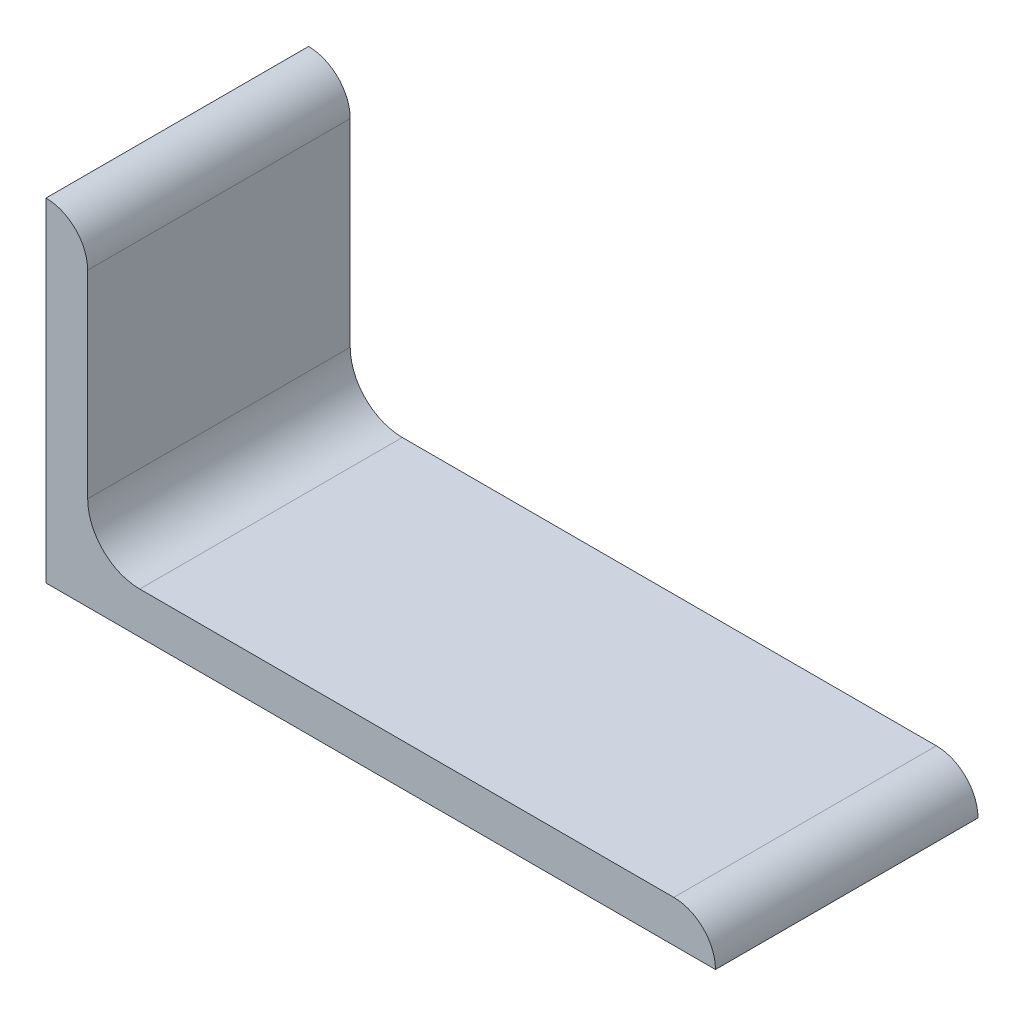
SolidWorks part; units mm, degrees
ref_plane "Alzado" through (0, 0, 0) normal (0, 0, 1) x (1, 0, 0)
ref_plane "Planta" through (0, 0, 0) normal (0, 1, 0) x (1, 0, 0)
ref_plane "Vista lateral" through (0, 0, 0) normal (1, 0, 0) x (0, 0, -1)
sketch "Croquis1" plane through (0, 0, 0) normal (1, 0, 0) x (0, 0, -1)
  line L0 (0, 0) -> (40, 0)
  dimension "D1" = 40
other "Hierro angular 3 X 2 X 0.25(1)"
ref_plane "Plano1" through (0, 0, 0) normal (0, 0, -1) x (0, 1, 0)
sketch "Sketch1" plane through (0, 0, 0) normal (0, 0, -1) x (0, 1, 0)
  line L0 (0, 0) -> (0, 102)
  line L1 (0, 102) -> (0.0051, 102)
  line L2 (6.35, 95.6551) -> (6.35, 14.2875)
  line L3 (14.2875, 6.35) -> (44.4551, 6.35)
  line L4 (50.8, 0.0051) -> (50.8, 0)
  line L5 (50.8, 0) -> (0, 0)
  arc A0 (50.8, 0.0051) -> (44.4551, 6.35) centre (44.4551, 0.0051) ccw
  arc A1 (0.0051, 102) -> (6.35, 95.6551) centre (0.0051, 95.6551) cw
  arc A2 (14.2875, 6.35) -> (6.35, 14.2875) centre (14.2875, 14.2875) cw
  point P10 (25.4, 0)
  point P14 (0, 51)
  point P15 (6.35, 51)
  point P16 (25.4, 6.35)
  point P17 (6.35, 102)
  point P18 (50.8, 6.35)
  point P19 (0, 0)
  dimension "D2" = 0.0051
  dimension "D3" = 102
  dimension "Radius_1" = 7.9375
  dimension "D1" = 6.35
  dimension "H_leg" = 50.8
